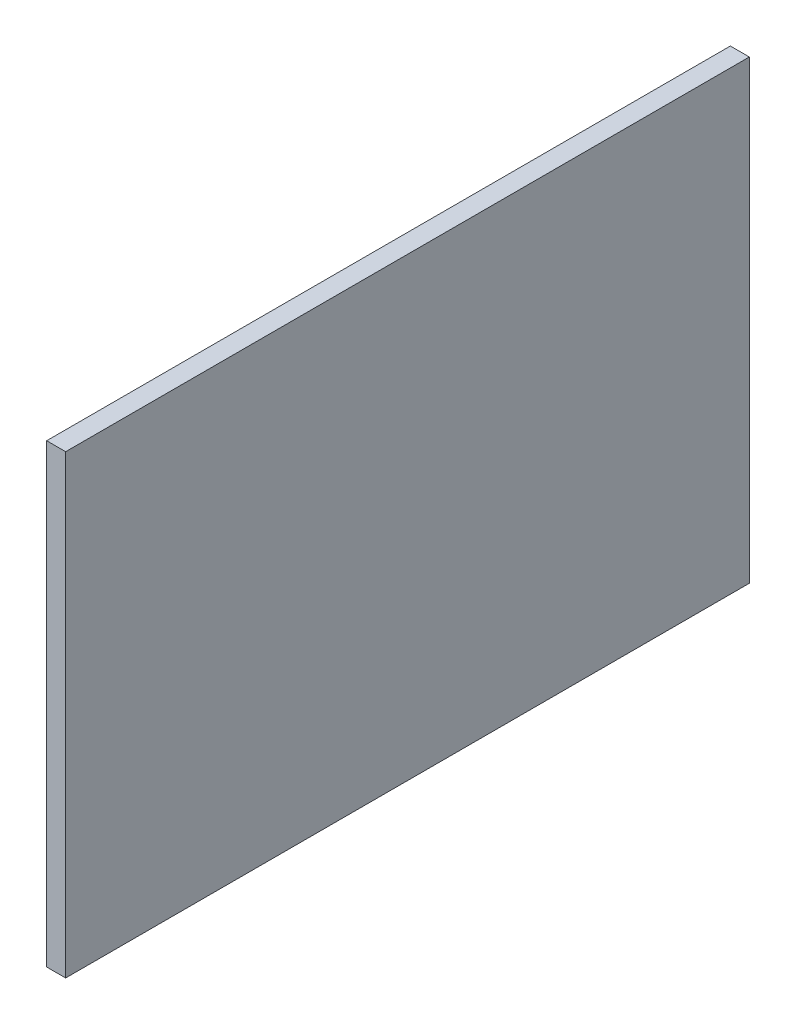
SolidWorks part; units mm, degrees
ref_plane "Front Plane" through (0, 0, 0) normal (0, 0, 1) x (1, 0, 0)
ref_plane "Top Plane" through (0, 0, 0) normal (0, 1, 0) x (1, 0, 0)
ref_plane "Right Plane" through (0, 0, 0) normal (1, 0, 0) x (0, 0, -1)
sketch "Sketch1" plane through (0, 0, 0) normal (1, 0, 0) x (0, 0, -1)
  line L1 (0, 0) -> (457.2, 0)
  line L2 (0, 0) -> (0, 304.8)
  line L3 (0, 304.8) -> (457.2, 304.8)
  line L4 (457.2, 0) -> (457.2, 304.8)
  dimension "D1" = 304.8
  dimension "D2" = 457.2
extrude "Boss-Extrude1" add sketch "Sketch1" along normal blind 12.7
